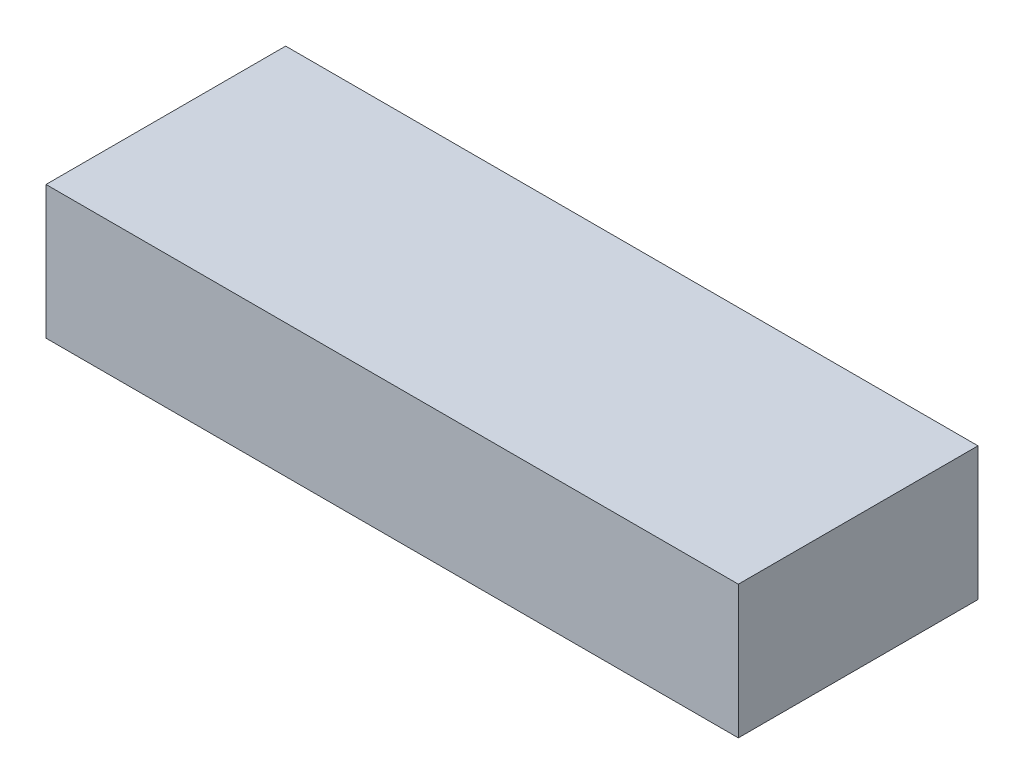
SolidWorks part; units mm, degrees
ref_plane "Спереди" through (0, 0, 0) normal (0, 0, 1) x (1, 0, 0)
ref_plane "Сверху" through (0, 0, 0) normal (0, 1, 0) x (1, 0, 0)
ref_plane "Справа" through (0, 0, 0) normal (1, 0, 0) x (0, 0, -1)
other "Configuration Table"
sketch "Эскиз1" plane through (0, 0, 0) normal (0, 1, 0) x (1, 0, 0)
  line L1 (65, -22.5) -> (-65, -22.5)
  line L2 (65, -22.5) -> (65, 22.5)
  line L3 (65, 22.5) -> (-65, 22.5)
  line L4 (-65, -22.5) -> (-65, 22.5)
  line L5 (65, -22.5) -> (-65, 22.5) construction
  line L6 (65, 22.5) -> (-65, -22.5) construction
  point P0 (0, 0)
extrude "Бобышка-Вытянуть1" add sketch "Эскиз1" along normal blind 25
